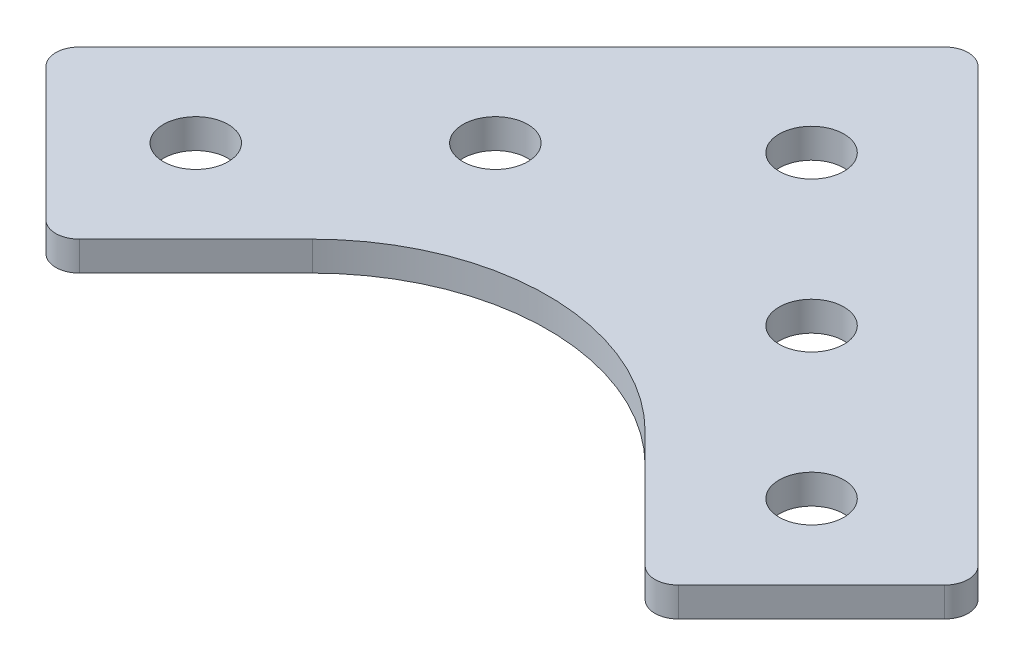
SolidWorks part; units mm, degrees
material "5052-H32"
ref_plane "Front Plane" through (0, 0, 0) normal (0, 0, 1) x (1, 0, 0)
ref_plane "Top Plane" through (0, 0, 0) normal (0, 1, 0) x (1, 0, 0)
ref_plane "Right Plane" through (0, 0, 0) normal (1, 0, 0) x (0, 0, -1)
sketch "Sketch1" plane through (0, 0, 0) normal (0, 1, 0) x (1, 0, 0)
  line L0 (-17.9605, 17.9605) -> (0, 35.921)
  line L5 (32.3289, -32.3289) -> (0, 0)
  line L6 (32.3289, -32.3289) -> (50.2894, -14.3684)
  line L7 (50.2894, -14.3684) -> (17.9605, 17.9605)
  line L9 (0, 0) -> (-32.3289, -32.3289)
  line L11 (-17.9605, 17.9605) -> (-50.2894, -14.3684)
  line L12 (-32.3289, -32.3289) -> (-50.2894, -14.3684)
  line L13 (0, 35.921) -> (17.9605, 17.9605)
  line L14 (-17.9605, 17.9605) -> (0, 0) construction
  line L15 (17.9605, 17.9605) -> (0, 0) construction
  line L16 (0, 0) -> (0, 35.921) construction
  dimension "D1" = 25.4
  dimension "D2" = 25.4
  dimension "D5" = 90
  dimension "D3" = 45.72
  dimension "D4" = 45.72
extrude "Boss-Extrude1" add sketch "Sketch1" along normal blind 3.175 contours L0 L13 L7 L6 L5 L9 L12 L11
sketch "Sketch2" plane through (0, 3.175, 0) normal (0, 1, 0) x (1, 0, 0)
  line L0 (-50.2894, -14.3684) -> (-32.3289, -32.3289) construction
  line L1 (-33.2269, -15.2664) -> (-41.3092, -23.3487) construction
  line L2 (50.2894, -14.3684) -> (32.3289, -32.3289) construction
  line L3 (33.2269, -15.2664) -> (41.3092, -23.3487) construction
  circle A0 centre (-33.2269, -15.2664) radius 3.4925
  circle A1 centre (33.2269, -15.2664) radius 3.4925
  dimension "D1" = 6.985
  dimension "D2" = 11.43
sketch "Sketch7" plane through (0, 3.175, 0) normal (0, 1, 0) x (1, 0, 0)
  line L0 (-50.2894, -14.3684) -> (-32.3289, -32.3289) construction
  line L1 (-33.2269, -15.2664) -> (-41.3092, -23.3487) construction
  line L2 (50.2894, -14.3684) -> (32.3289, -32.3289) construction
  line L3 (33.2269, -15.2664) -> (41.3092, -23.3487) construction
  circle A0 centre (-33.2269, -15.2664) radius 3.4925
  circle A1 centre (33.2269, -15.2664) radius 3.4925
  dimension "D1" = 6.985
  dimension "D2" = 11.43
extrude "Cut-Extrude2" cut sketch "Sketch2" against normal blind 3.175 contours A0
pattern_linear "LPattern5" count 2 spacing 22.86 along (0.7071, 0, -0.7071) of "Cut-Extrude2"
extrude "Cut-Extrude3" cut sketch "Sketch7" against normal blind 3.175 contours A1
pattern_linear "LPattern6" count 3 spacing 22.86 along (-0.7071, 0, -0.7071) of "Cut-Extrude3"
fillet "Fillet1" radius 2.54 5 edges at (0, 1.5875, -35.921) (50.2894, 1.5875, 14.3684) (32.3289, 1.5875, 32.3289) (-32.3289, 1.5875, 32.3289) (-50.2894, 1.5875, 14.3684)
fillet "Fillet2" radius 25.4 1 edges at (0, 1.5875, 0)
equation "\"InnerAngle\"= 90"
equation "\"StockThickness\"= .125in"
equation "\"HoleDiameter\"= .275in"
equation "\"BarWidth\"= 1in"
equation "\"HoleSpacing\"=0.9"
equation "\"AdditionalHoleCount\"= 1"
equation "\"D1@Sketch1\"=\"BarWidth\""
equation "\"D2@Sketch1\"= \"BarWidth\""
equation "\"WingLength\"= ( \"AdditionalHoleCount\" + 1 ) * \"HoleSpacing\""
equation "\"D5@Sketch1\"=\"InnerAngle\""
equation "\"D1@Boss-Extrude1\"=\"StockThickness\""
equation "\"D1@Sketch2\"=\"HoleDiameter\""
equation "\"D2@Sketch2\"=\"HoleSpacing\"/2"
equation "\"D3@LPattern5\"=\"HoleSpacing\""
equation "\"D1@LPattern5\"=\"AdditionalHoleCount\"+1"
equation "\"D2@Sketch7\"=\"HoleSpacing\"/2"
equation "\"D1@Sketch7\"=\"HoleDiameter\""
equation "\"D3@LPattern6\"=\"HoleSpacing\""
equation "\"D1@LPattern6\"=\"AdditionalHoleCount\"+2"
equation "\"D3@Sketch1\"=\"WingLength\""
equation "\"D4@Sketch1\"=\"WingLength\""
